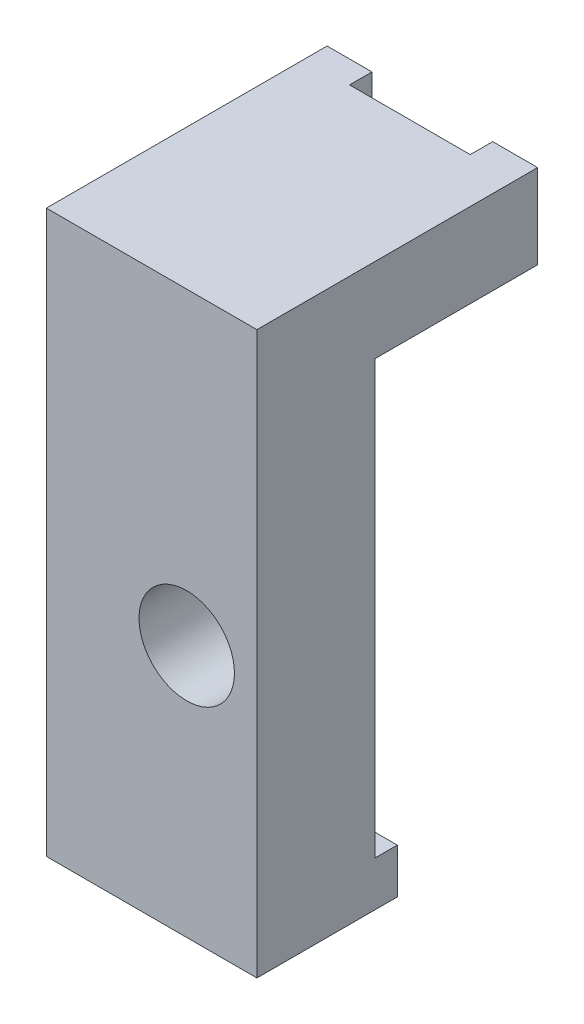
SolidWorks part; units mm, degrees
ref_plane "Front Plane" through (0, 0, 0) normal (0, 0, 1) x (1, 0, 0)
ref_plane "Top Plane" through (0, 0, 0) normal (0, 1, 0) x (1, 0, 0)
ref_plane "Right Plane" through (0, 0, 0) normal (1, 0, 0) x (0, 0, -1)
sketch "Sketch1" plane through (0, 0, 0) normal (0, 0, 1) x (1, 0, 0)
  line L1 (-4.7625, 12.7) -> (4.7625, 12.7)
  line L2 (-4.7625, 12.7) -> (-4.7625, -12.7)
  line L3 (-4.7625, -12.7) -> (4.7625, -12.7)
  line L4 (4.7625, 12.7) -> (4.7625, -12.7)
  line L5 (-4.7625, 12.7) -> (4.7625, -12.7) construction
  line L6 (-4.7625, -12.7) -> (4.7625, 12.7) construction
  point P0 (0, 0)
  dimension "D1" = 25.4
  dimension "D2" = 9.525
extrude "Boss-Extrude1" add sketch "Sketch1" along normal mid plane 12.7
sketch "Sketch2" plane through (4.7625, 0, 0) normal (1, 0, 0) x (0, 0, -1)
  line L0 (-6.35, -12.7) -> (-6.35, 12.7) construction
  line L1 (6.35, -12.7) -> (0, -12.7)
  line L2 (6.35, -12.7) -> (6.35, 8.89)
  line L3 (6.35, 8.89) -> (0, 8.89)
  line L4 (0, -12.7) -> (0, 8.89)
  line L5 (-6.35, 12.7) -> (6.35, 12.7) construction
  dimension "D1" = 6.35
  dimension "D2" = 3.81
extrude "Cut-Extrude1" cut sketch "Sketch2" against normal up to next
sketch "Sketch3" plane through (0, 0, 6.35) normal (0, 0, 1) x (1, 0, 0)
  line L0 (-4.7625, -12.7) -> (4.7625, -12.7) construction
  line L2 (4.7625, -12.7) -> (4.7625, 12.7) construction
  circle A0 centre (1.5875, -1.27) radius 2.159
  dimension "D1" = 11.43
  dimension "D2" = 3.175
extrude "Cut-Extrude2" cut sketch "Sketch3" against normal up to next
sketch "Sketch4" plane through (0, 12.7, 0) normal (0, 1, 0) x (1, 0, 0)
  line L0 (4.7625, 6.35) -> (-4.7625, 6.35) construction
  line L1 (2.7305, 6.35) -> (-2.7305, 6.35)
  line L2 (2.7305, 6.35) -> (2.7305, 5.334)
  line L3 (2.7305, 5.334) -> (-2.7305, 5.334)
  line L4 (-2.7305, 6.35) -> (-2.7305, 5.334)
  line L5 (-4.7625, -6.35) -> (-4.7625, 6.35) construction
  line L6 (4.7625, -6.35) -> (4.7625, 6.35) construction
  dimension "D1" = 2.032
  dimension "D2" = 2.032
  dimension "D3" = 1.016
extrude "Cut-Extrude3" cut sketch "Sketch4" against normal up to next
sketch "Sketch5" plane through (4.7625, 0, 0) normal (1, 0, 0) x (0, 0, -1)
  line L0 (0, 8.89) -> (0, -12.7) construction
  line L1 (0, -10.668) -> (-1.016, -10.668)
  line L2 (0, -10.668) -> (0, 8.89)
  line L3 (0, 8.89) -> (-1.016, 8.89)
  line L4 (-1.016, -10.668) -> (-1.016, 8.89)
  line L5 (-6.35, -12.7) -> (0, -12.7) construction
  line L6 (6.35, 8.89) -> (0, 8.89) construction
  dimension "D1" = 2.032
  dimension "D2" = 1.016
extrude "Cut-Extrude4" cut sketch "Sketch5" against normal through all
